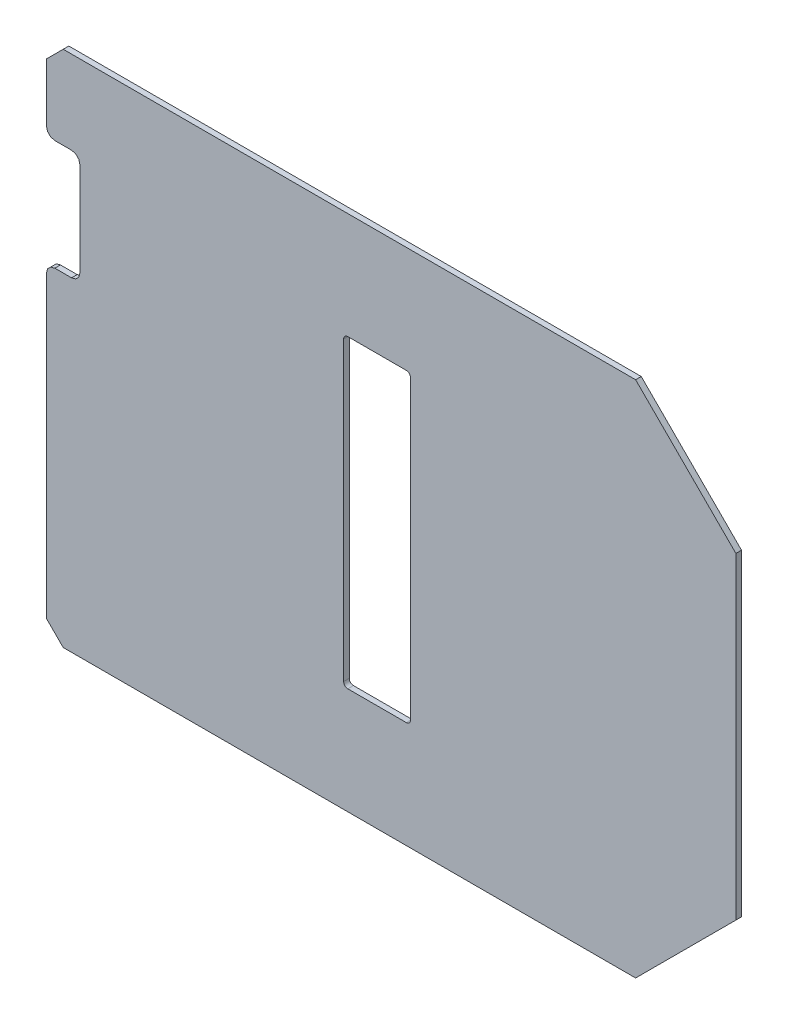
SolidWorks part; units mm, degrees
ref_plane "Front Plane" through (0, 0, 0) normal (0, 0, 1) x (1, 0, 0)
ref_plane "Top Plane" through (0, 0, 0) normal (0, 1, 0) x (1, 0, 0)
ref_plane "Right Plane" through (0, 0, 0) normal (1, 0, 0) x (0, 0, -1)
ref_plane "Plane1" through (0, 0, 0) normal (0, 0, -1) x (-1, 0, 0)
sketch "Sketch1" plane through (0, 0, 0) normal (0, 0, -1) x (-1, 0, 0)
  line L0 (372.5, 200.3493) -> (373.8397, 205.3493)
  line L1 (373.8397, 205.3493) -> (377.5, 209.0095)
  line L2 (377.5, 209.0095) -> (382.5, 210.3492)
  line L3 (382.5, 210.3492) -> (402.5, 210.3492)
  line L4 (402.5, 210.3492) -> (407.5, 211.689)
  line L5 (407.5, 211.689) -> (411.1603, 215.3493)
  line L6 (411.1603, 215.3493) -> (412.5, 220.3493)
  line L7 (412.5, 220.3493) -> (412.5, 290)
  line L8 (412.5, 290) -> (392.5, 310)
  line L9 (392.5, 310) -> (-292.5, 310)
  line L10 (-292.5, 310) -> (-412.5, 190)
  line L11 (-412.5, 190) -> (-412.5, -190)
  line L12 (-412.5, -190) -> (-292.5, -310)
  line L13 (-292.5, -310) -> (392.5, -310)
  line L14 (392.5, -310) -> (412.5, -290)
  line L15 (412.5, -290) -> (412.5, 68.1131)
  line L16 (412.5, 68.1131) -> (411.1603, 73.1131)
  line L17 (411.1603, 73.1131) -> (407.5, 76.7734)
  line L18 (407.5, 76.7734) -> (402.5, 78.1131)
  line L19 (402.5, 78.1131) -> (382.5, 78.1131)
  line L20 (382.5, 78.1131) -> (377.5, 79.4529)
  line L21 (377.5, 79.4529) -> (373.8397, 83.1131)
  line L22 (373.8397, 83.1131) -> (372.5, 88.1131)
  line L23 (372.5, 88.1131) -> (372.5, 200.3493)
extrude "Boss-Extrude1" add sketch "Sketch1" against normal blind 6.7208
sketch "Sketch2" plane through (0, 0, 0) normal (0, 0, -1) x (-1, 0, 0)
  line L0 (-412.5, 190) -> (-412.5, -190) construction
  line L1 (-23.1, 182.5) -> (56.9, 182.5)
  line L2 (-23.1, 182.5) -> (-23.1, -182.5)
  line L3 (-23.1, -182.5) -> (56.9, -182.5)
  line L4 (56.9, 182.5) -> (56.9, -182.5)
  line L5 (412.5, -290) -> (412.5, 68.1131) construction
  point P4 (-23.1, 0)
  point P7 (-412.5, 0)
  dimension "D1" = 355.6
  dimension "D2" = 80
  dimension "D3" = 365
extrude "Cut-Extrude1" cut sketch "Sketch2" against normal through all
fillet "Fillet1" radius 5 4 edges at (-56.9, -182.5, 3.3604) (23.1, -182.5, 3.3604) (-56.9, 182.5, 3.3604) (23.1, 182.5, 3.3604)
